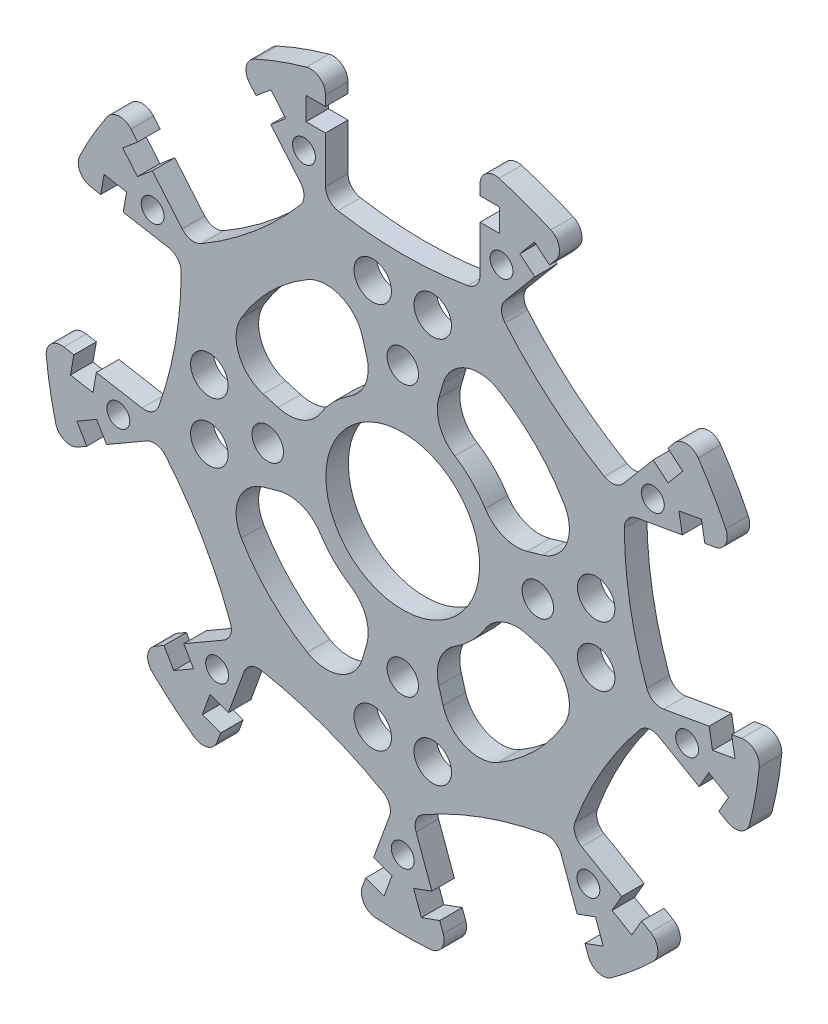
SolidWorks part; units mm, degrees
material "5052-O"
ref_plane "正面" through (0, 0, 0) normal (0, 0, 1) x (1, 0, 0)
ref_plane "平面" through (0, 0, 0) normal (0, 1, 0) x (1, 0, 0)
ref_plane "右側面" through (0, 0, 0) normal (1, 0, 0) x (0, 0, -1)
sketch "ｽｹｯﾁ1" plane through (0, 0, 0) normal (0, 0, 1) x (1, 0, 0)
  circle A0 centre (0, 0) radius 47.75
  dimension "D1" = 95.5
extrude "ﾎﾞｽ - 押し出し1" add sketch "ｽｹｯﾁ1" along normal blind 3
sketch "ｽｹｯﾁ2" plane through (0, 0, 3) normal (0, 0, 1) x (1, 0, 0)
  line L0 (-10.3, 46.6259) -> (-10.3, 42.705)
  line L1 (10.3, 46.6259) -> (10.3, 42.705)
  line L2 (0, 47.75) -> (0, -47.75) construction
  line L3 (-10.3, 39.655) -> (-10.3, 31.8257)
  line L4 (12.9, 39.655) -> (10.3, 39.655)
  line L5 (12.9, 39.655) -> (12.9, 42.705)
  line L6 (12.9, 42.705) -> (10.3, 42.705)
  line L7 (-12.9, 39.655) -> (-12.9, 42.705)
  line L8 (12.9, 39.655) -> (-12.9, 42.705) construction
  line L9 (12.9, 42.705) -> (-12.9, 39.655) construction
  line L10 (-10.3, 39.655) -> (-12.9, 39.655)
  line L11 (-10.3, 42.705) -> (-12.9, 42.705)
  line L12 (10.3, 39.655) -> (10.3, 31.8257)
  line L13 (0, 30.78) -> (0, 41.18) construction
  line L14 (17.5995, 36.9982) -> (12.5669, 31.0006)
  line L15 (17.5995, 36.9982) -> (15.6078, 38.6695)
  line L16 (15.6078, 38.6695) -> (17.5683, 41.0059)
  line L17 (19.56, 39.3346) -> (17.5683, 41.0059)
  line L18 (22.0803, 42.3382) -> (19.56, 39.3346)
  line L19 (37.8608, 29.0968) -> (35.3405, 26.0932)
  line L20 (37.3322, 24.422) -> (35.3405, 26.0932)
  line L21 (35.3717, 22.0855) -> (37.3322, 24.422)
  line L22 (35.3717, 22.0855) -> (33.38, 23.7568)
  line L23 (33.38, 23.7568) -> (28.3474, 17.7592)
  line L24 (37.264, 17.0295) -> (29.5536, 15.67)
  line L25 (37.264, 17.0295) -> (36.8125, 19.59)
  line L26 (36.8125, 19.59) -> (39.8162, 20.1197)
  line L27 (40.2676, 17.5592) -> (39.8162, 20.1197)
  line L28 (44.1289, 18.24) -> (40.2676, 17.5592)
  line L29 (47.7061, -2.047) -> (43.8448, -2.7279)
  line L30 (44.2963, -5.2884) -> (43.8448, -2.7279)
  line L31 (41.2926, -5.818) -> (44.2963, -5.2884)
  line L32 (41.2926, -5.818) -> (40.8411, -3.2575)
  line L33 (40.8411, -3.2575) -> (33.1308, -4.617)
  line L34 (39.4922, -10.9074) -> (32.7119, -6.9928)
  line L35 (39.4922, -10.9074) -> (40.7922, -8.6558)
  line L36 (40.7922, -8.6558) -> (43.4336, -10.1808)
  line L37 (42.1336, -12.4324) -> (43.4336, -10.1808)
  line L38 (45.5292, -14.3929) -> (42.1336, -12.4324)
  line L39 (35.2292, -32.233) -> (31.8336, -30.2726)
  line L40 (30.5336, -32.5242) -> (31.8336, -30.2726)
  line L41 (27.8922, -30.9992) -> (30.5336, -32.5242)
  line L42 (27.8922, -30.9992) -> (29.1922, -28.7476)
  line L43 (29.1922, -28.7476) -> (22.4119, -24.8329)
  line L44 (23.2416, -33.7407) -> (20.5639, -26.3836)
  line L45 (23.2416, -33.7407) -> (25.6848, -32.8515)
  line L46 (25.6848, -32.8515) -> (26.728, -35.7175)
  line L47 (24.2848, -36.6068) -> (26.728, -35.7175)
  line L48 (25.6258, -40.2912) -> (24.2848, -36.6068)
  line L49 (6.2682, -47.3368) -> (4.9271, -43.6524)
  line L50 (2.4839, -44.5416) -> (4.9271, -43.6524)
  line L51 (1.4408, -41.6756) -> (2.4839, -44.5416)
  line L52 (1.4408, -41.6756) -> (3.884, -40.7863)
  line L53 (3.884, -40.7863) -> (1.2062, -33.4292)
  line L54 (-3.884, -40.7863) -> (-1.2062, -33.4292)
  line L55 (-3.884, -40.7863) -> (-1.4408, -41.6756)
  line L56 (-1.4408, -41.6756) -> (-2.4839, -44.5416)
  line L57 (-4.9271, -43.6524) -> (-2.4839, -44.5416)
  line L58 (-6.2682, -47.3368) -> (-4.9271, -43.6524)
  line L59 (-25.6258, -40.2912) -> (-24.2848, -36.6068)
  line L60 (-26.728, -35.7175) -> (-24.2848, -36.6068)
  line L61 (-25.6848, -32.8515) -> (-26.728, -35.7175)
  line L62 (-25.6848, -32.8515) -> (-23.2416, -33.7407)
  line L63 (-23.2416, -33.7407) -> (-20.5639, -26.3836)
  line L64 (-29.1922, -28.7476) -> (-22.4119, -24.8329)
  line L65 (-29.1922, -28.7476) -> (-27.8922, -30.9992)
  line L66 (-27.8922, -30.9992) -> (-30.5336, -32.5242)
  line L67 (-31.8336, -30.2726) -> (-30.5336, -32.5242)
  line L68 (-35.2292, -32.233) -> (-31.8336, -30.2726)
  line L69 (-45.5292, -14.3929) -> (-42.1336, -12.4324)
  line L70 (-43.4336, -10.1808) -> (-42.1336, -12.4324)
  line L71 (-40.7922, -8.6558) -> (-43.4336, -10.1808)
  line L72 (-40.7922, -8.6558) -> (-39.4922, -10.9074)
  line L73 (-39.4922, -10.9074) -> (-32.7119, -6.9928)
  line L74 (-40.8411, -3.2575) -> (-33.1308, -4.617)
  line L75 (-40.8411, -3.2575) -> (-41.2926, -5.818)
  line L76 (-41.2926, -5.818) -> (-44.2963, -5.2884)
  line L77 (-43.8448, -2.7279) -> (-44.2963, -5.2884)
  line L78 (-47.7061, -2.047) -> (-43.8448, -2.7279)
  line L79 (-44.1289, 18.24) -> (-40.2676, 17.5592)
  line L80 (-39.8162, 20.1197) -> (-40.2676, 17.5592)
  line L81 (-36.8125, 19.59) -> (-39.8162, 20.1197)
  line L82 (-36.8125, 19.59) -> (-37.264, 17.0295)
  line L83 (-37.264, 17.0295) -> (-29.5536, 15.67)
  line L84 (-33.38, 23.7568) -> (-28.3474, 17.7592)
  line L85 (-33.38, 23.7568) -> (-35.3717, 22.0855)
  line L86 (-35.3717, 22.0855) -> (-37.3322, 24.422)
  line L87 (-35.3405, 26.0932) -> (-37.3322, 24.422)
  line L88 (-37.8608, 29.0968) -> (-35.3405, 26.0932)
  line L89 (-22.0803, 42.3382) -> (-19.56, 39.3346)
  line L90 (-17.5683, 41.0059) -> (-19.56, 39.3346)
  line L91 (-15.6078, 38.6695) -> (-17.5683, 41.0059)
  line L92 (-15.6078, 38.6695) -> (-17.5995, 36.9982)
  line L93 (-17.5995, 36.9982) -> (-12.5669, 31.0006)
  circle A0 centre (0, 0) radius 47.75 construction
  arc A1 (-10.3, 46.6259) -> (10.3, 46.6259) centre (0, 0) cw
  arc A2 (-10.3, 31.8257) -> (10.3, 31.8257) centre (0, 82.03) ccw
  arc A3 (12.5669, 31.0006) -> (28.3474, 17.7592) centre (52.7279, 62.8386) ccw
  arc A4 (22.0803, 42.3382) -> (37.8608, 29.0968) centre (0, 0) cw
  arc A5 (29.5536, 15.67) -> (33.1308, -4.617) centre (80.7838, 14.2444) ccw
  arc A6 (44.1289, 18.24) -> (47.7061, -2.047) centre (0, 0) cw
  arc A7 (32.7119, -6.9928) -> (22.4119, -24.8329) centre (71.0401, -41.015) ccw
  arc A8 (45.5292, -14.3929) -> (35.2292, -32.233) centre (0, 0) cw
  arc A9 (20.5639, -26.3836) -> (1.2062, -33.4292) centre (28.0559, -77.083) ccw
  arc A10 (25.6258, -40.2912) -> (6.2682, -47.3368) centre (0, 0) cw
  arc A11 (-1.2062, -33.4292) -> (-20.5639, -26.3836) centre (-28.0559, -77.083) ccw
  arc A12 (-6.2682, -47.3368) -> (-25.6258, -40.2912) centre (0, 0) cw
  arc A13 (-22.4119, -24.8329) -> (-32.7119, -6.9928) centre (-71.0401, -41.015) ccw
  arc A14 (-35.2292, -32.233) -> (-45.5292, -14.3929) centre (0, 0) cw
  arc A15 (-33.1308, -4.617) -> (-29.5536, 15.67) centre (-80.7838, 14.2444) ccw
  arc A16 (-47.7061, -2.047) -> (-44.1289, 18.24) centre (0, 0) cw
  arc A17 (-28.3474, 17.7592) -> (-12.5669, 31.0006) centre (-52.7279, 62.8386) ccw
  arc A18 (-37.8608, 29.0968) -> (-22.0803, 42.3382) centre (0, 0) cw
  point P11 (0, 41.18)
  point P139 (0, 0)
  dimension "D2" = 20.6
  dimension "D7" = 51.25
  dimension "D1" = 41.18
  dimension "D3" = 10.3
  dimension "D4" = 3.05
  dimension "D5" = 25.8
  dimension "D6" = 10.4
  dimension "D8" = 9
extrude "ｶｯﾄ - 押し出し1" cut sketch "ｽｹｯﾁ2" against normal through all
fillet "ﾌｨﾚｯﾄ2" radius 2 36 edges at (-12.5669, 31.0006, 1.5) (-28.3474, 17.7592, 1.5) (-29.5536, 15.67, 1.5) (-33.1308, -4.617, 1.5) (-32.7119, -6.9928, 1.5) (-22.4119, -24.8329, 1.5) (-20.5639, -26.3836, 1.5) (-1.2062, -33.4292, 1.5) (1.2062, -33.4292, 1.5) (20.5639, -26.3836, 1.5) (32.7119, -6.9928, 1.5) (22.4119, -24.8329, 1.5) (33.1308, -4.617, 1.5) (29.5536, 15.67, 1.5) (28.3474, 17.7592, 1.5) (12.5669, 31.0006, 1.5) (10.3, 31.8257, 1.5) (-10.3, 31.8257, 1.5) (35.2292, -32.233, 1.5) (25.6258, -40.2912, 1.5) (6.2682, -47.3368, 1.5) (-6.2682, -47.3368, 1.5) (-25.6258, -40.2912, 1.5) (-35.2292, -32.233, 1.5) (-45.5292, -14.3929, 1.5) (-47.7061, -2.047, 1.5) (-44.1289, 18.24, 1.5) (-37.8608, 29.0968, 1.5) (-22.0803, 42.3382, 1.5) (-10.3, 46.6259, 1.5) (22.0803, 42.3382, 1.5) (10.3, 46.6259, 1.5) (37.8608, 29.0968, 1.5) (44.1289, 18.24, 1.5) (47.7061, -2.047, 1.5) (45.5292, -14.3929, 1.5)
sketch "ｽｹｯﾁ3" plane through (0, 0, 3) normal (0, 0, 1) x (1, 0, 0)
  line L0 (0, 0) -> (0, -38.5) construction
  line L1 (0, 0) -> (-24.7473, -29.4927) construction
  line L2 (0, 0) -> (-37.9151, -6.6855) construction
  line L3 (0, 0) -> (-33.342, 19.25) construction
  line L4 (0, 0) -> (-13.1678, 36.1782) construction
  line L5 (0, 0) -> (13.1678, 36.1782) construction
  line L6 (0, 0) -> (33.342, 19.25) construction
  line L7 (0, 0) -> (37.9151, -6.6855) construction
  line L8 (0, 0) -> (24.7473, -29.4927) construction
  circle A2 centre (0, -38.5) radius 1.525
  circle A3 centre (0, 0) radius 38.5 construction
  circle A4 centre (-24.7473, -29.4927) radius 1.525
  circle A5 centre (0, 0) radius 38.5 construction
  circle A6 centre (-37.9151, -6.6855) radius 1.525
  circle A7 centre (0, 0) radius 38.5 construction
  circle A8 centre (-33.342, 19.25) radius 1.525
  circle A9 centre (0, 0) radius 38.5 construction
  circle A10 centre (-13.1678, 36.1782) radius 1.525
  circle A11 centre (0, 0) radius 38.5 construction
  circle A12 centre (13.1678, 36.1782) radius 1.525
  circle A13 centre (0, 0) radius 38.5 construction
  circle A14 centre (33.342, 19.25) radius 1.525
  circle A15 centre (0, 0) radius 38.5 construction
  circle A16 centre (37.9151, -6.6855) radius 1.525
  circle A17 centre (0, 0) radius 38.5 construction
  circle A18 centre (24.7473, -29.4927) radius 1.525
  circle A19 centre (0, 0) radius 38.5 construction
  point P10 (0, 0)
  point P32 (0, 0)
  dimension "D1" = 3.05
  dimension "D2" = 77
  dimension "D3" = 9
extrude "ｶｯﾄ - 押し出し2" cut sketch "ｽｹｯﾁ3" against normal through all
sketch "ｽｹｯﾁ4" plane through (0, 0, 0) normal (0, 0, -1) x (-1, 0, 0)
  line L0 (0, -48.3338) -> (0, 30.1962) construction
  circle A0 centre (18, 0) radius 2.1
  circle A1 centre (0, -18) radius 2.1
  circle A2 centre (0, 18) radius 2.1
  circle A3 centre (0, 0) radius 18 construction
  circle A4 centre (0, 0) radius 10.25
  circle A5 centre (-18, 0) radius 2.1
  point P11 (0, 0)
  dimension "D2" = 4.2
  dimension "D4" = 20.5
  dimension "D1" = 18
  dimension "D3" = 4
extrude "ｶｯﾄ - 押し出し3" cut sketch "ｽｹｯﾁ4" against normal through all
sketch "ｽｹｯﾁ7" plane through (0, 0, 0) normal (0, 0, -1) x (-1, 0, 0)
  line L0 (0, 0) -> (-31.5531, 0) construction
  line L1 (0, 0) -> (-30.3124, 5.3449) construction
  line L3 (0, 0) -> (-5.4791, 31.0737) construction
  line L9 (0, 0) -> (0, 18) construction
  line L10 (-3.6111, 12.4884) -> (-6.9444, 24.0161)
  line L11 (0, 18) -> (-4.8032, 16.6111) construction
  line L12 (-12.4884, 3.6111) -> (-24.0161, 6.9444)
  line L13 (-18, 0) -> (-16.6111, 4.8032) construction
  arc A1 (-32.5341, -3.0337) -> (-29.5345, 13.978) centre (-80.7838, 14.2444) ccw construction
  arc A4 (-8.6371, 31.513) -> (8.6371, 31.513) centre (0, 82.03) ccw construction
  arc A7 (-24.0161, 6.9444) -> (-6.9444, 24.0161) centre (0, 0) cw
  arc A8 (-12.4884, 3.6111) -> (-3.6111, 12.4884) centre (0, 0) cw
  dimension "D1" = 5
  dimension "D3" = 5
  dimension "D4" = 25
  dimension "D5" = 13
  dimension "D2" = 70
  dimension "D6" = 16.128
  dimension "D7" = 16.128
extrude "ｶｯﾄ - 押し出し4" cut sketch "ｽｹｯﾁ7" against normal through all
fillet "ﾌｨﾚｯﾄ3" radius 5 4 edges at (12.4884, 3.6111, 1.5) (24.0161, 6.9444, 1.5) (6.9444, 24.0161, 1.5) (3.6111, 12.4884, 1.5)
pattern_circular "円形ﾊﾟﾀｰﾝ1" count 4 over 360 about axis through (0, 0, 0) along (0, 0, 1) of "ﾌｨﾚｯﾄ3", "ｶｯﾄ - 押し出し4"
sketch "ｽｹｯﾁ8" plane through (0, 0, 0) normal (0, 0, -1) x (-1, 0, 0)
  line L0 (0, -47.75) -> (0, 30.78) construction
  line L1 (-9.9226, 25.78) -> (9.5126, 25.78) construction
  arc A0 (-3.6667, -47.609) -> (3.6667, -47.609) centre (0, 0) ccw construction
  arc A1 (-8.6371, 31.513) -> (8.6371, 31.513) centre (0, 82.03) ccw construction
  circle A2 centre (-4, 25.78) radius 2.5
  circle A3 centre (4, 25.78) radius 2.5
  dimension "D2" = 5
  dimension "D3" = 5
  dimension "D4" = 4
  dimension "D5" = 8
  dimension "D1" = 5
extrude "ｶｯﾄ - 押し出し5" cut sketch "ｽｹｯﾁ8" against normal through all
pattern_circular "円形ﾊﾟﾀｰﾝ2" count 4 over 360 about axis through (0, 0, 0) along (0, 0, 1) of "ｶｯﾄ - 押し出し5"
